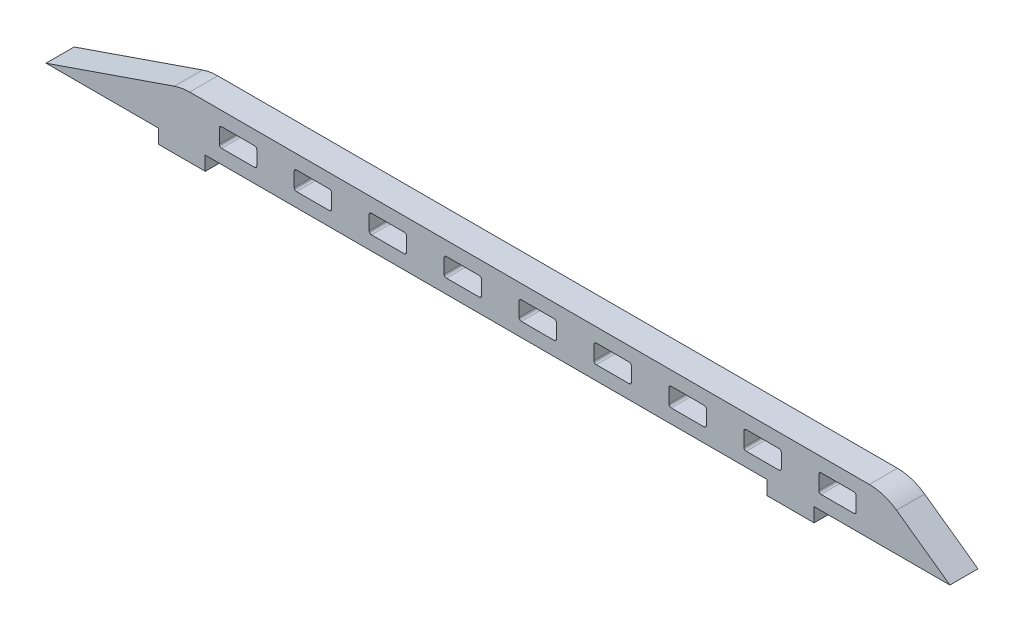
SolidWorks part; units mm, degrees
ref_plane "Front Plane" through (0, 0, 0) normal (0, 0, 1) x (1, 0, 0)
ref_plane "Top Plane" through (0, 0, 0) normal (0, 1, 0) x (1, 0, 0)
ref_plane "Right Plane" through (0, 0, 0) normal (1, 0, 0) x (0, 0, -1)
sketch "Sketch1" plane through (0, 0, 0) normal (0, 0, 1) x (1, 0, 0)
  line L0 (0, 0) -> (24, 0)
  line L1 (24, 0) -> (24, -3)
  line L2 (24, -3) -> (34, -3)
  line L3 (34, -3) -> (34, 0)
  line L4 (34, 0) -> (154, 0)
  line L5 (154, 0) -> (154, -3)
  line L6 (154, -3) -> (164, -3)
  line L7 (164, -3) -> (164, 0)
  line L8 (164, 0) -> (193, 0)
  line L9 (0, 0) -> (29, 10)
  line L10 (29, 10) -> (179, 10)
  line L11 (179, 10) -> (193, 0)
  line L12 (53.5, 7) -> (60.5, 7)
  line L13 (37.5, 7) -> (44.5, 7)
  line L14 (37, 6.5) -> (37, 3.5)
  line L15 (37.5, 3) -> (44.5, 3)
  line L16 (45, 6.5) -> (45, 3.5)
  line L17 (53, 6.5) -> (53, 3.5)
  line L18 (53.5, 3) -> (60.5, 3)
  line L19 (61, 6.5) -> (61, 3.5)
  line L20 (69.5, 7) -> (76.5, 7)
  line L21 (69, 6.5) -> (69, 3.5)
  line L22 (69.5, 3) -> (76.5, 3)
  line L23 (77, 6.5) -> (77, 3.5)
  line L24 (85.5, 7) -> (92.5, 7)
  line L25 (85, 6.5) -> (85, 3.5)
  line L26 (85.5, 3) -> (92.5, 3)
  line L27 (93, 6.5) -> (93, 3.5)
  line L28 (101.5, 7) -> (108.5, 7)
  line L29 (101, 6.5) -> (101, 3.5)
  line L30 (101.5, 3) -> (108.5, 3)
  line L31 (109, 6.5) -> (109, 3.5)
  line L32 (117.5, 7) -> (124.5, 7)
  line L33 (117, 6.5) -> (117, 3.5)
  line L34 (117.5, 3) -> (124.5, 3)
  line L35 (125, 6.5) -> (125, 3.5)
  line L36 (133.5, 7) -> (140.5, 7)
  line L37 (133, 6.5) -> (133, 3.5)
  line L38 (133.5, 3) -> (140.5, 3)
  line L39 (141, 6.5) -> (141, 3.5)
  line L40 (149.5, 7) -> (156.5, 7)
  line L41 (149, 6.5) -> (149, 3.5)
  line L42 (149.5, 3) -> (156.5, 3)
  line L43 (157, 6.5) -> (157, 3.5)
  line L44 (165.5, 7) -> (172.5, 7)
  line L45 (165, 6.5) -> (165, 3.5)
  line L46 (165.5, 3) -> (172.5, 3)
  line L47 (173, 6.5) -> (173, 3.5)
  arc A0 (44.5, 7) -> (45, 6.5) centre (44.5, 6.5) cw
  arc A1 (44.5, 3) -> (45, 3.5) centre (44.5, 3.5) ccw
  arc A2 (37, 3.5) -> (37.5, 3) centre (37.5, 3.5) ccw
  arc A3 (37.5, 7) -> (37, 6.5) centre (37.5, 6.5) ccw
  arc A4 (53.5, 7) -> (53, 6.5) centre (53.5, 6.5) ccw
  arc A5 (53, 3.5) -> (53.5, 3) centre (53.5, 3.5) ccw
  arc A6 (60.5, 3) -> (61, 3.5) centre (60.5, 3.5) ccw
  arc A7 (60.5, 7) -> (61, 6.5) centre (60.5, 6.5) cw
  arc A8 (69.5, 7) -> (69, 6.5) centre (69.5, 6.5) ccw
  arc A9 (69, 3.5) -> (69.5, 3) centre (69.5, 3.5) ccw
  arc A10 (76.5, 3) -> (77, 3.5) centre (76.5, 3.5) ccw
  arc A11 (76.5, 7) -> (77, 6.5) centre (76.5, 6.5) cw
  arc A12 (85.5, 7) -> (85, 6.5) centre (85.5, 6.5) ccw
  arc A13 (85, 3.5) -> (85.5, 3) centre (85.5, 3.5) ccw
  arc A14 (92.5, 3) -> (93, 3.5) centre (92.5, 3.5) ccw
  arc A15 (92.5, 7) -> (93, 6.5) centre (92.5, 6.5) cw
  arc A16 (101.5, 7) -> (101, 6.5) centre (101.5, 6.5) ccw
  arc A17 (101, 3.5) -> (101.5, 3) centre (101.5, 3.5) ccw
  arc A18 (108.5, 3) -> (109, 3.5) centre (108.5, 3.5) ccw
  arc A19 (108.5, 7) -> (109, 6.5) centre (108.5, 6.5) cw
  arc A20 (117.5, 7) -> (117, 6.5) centre (117.5, 6.5) ccw
  arc A21 (117, 3.5) -> (117.5, 3) centre (117.5, 3.5) ccw
  arc A22 (124.5, 3) -> (125, 3.5) centre (124.5, 3.5) ccw
  arc A23 (124.5, 7) -> (125, 6.5) centre (124.5, 6.5) cw
  arc A24 (133.5, 7) -> (133, 6.5) centre (133.5, 6.5) ccw
  arc A25 (133, 3.5) -> (133.5, 3) centre (133.5, 3.5) ccw
  arc A26 (140.5, 3) -> (141, 3.5) centre (140.5, 3.5) ccw
  arc A27 (140.5, 7) -> (141, 6.5) centre (140.5, 6.5) cw
  arc A28 (149.5, 7) -> (149, 6.5) centre (149.5, 6.5) ccw
  arc A29 (149, 3.5) -> (149.5, 3) centre (149.5, 3.5) ccw
  arc A30 (156.5, 3) -> (157, 3.5) centre (156.5, 3.5) ccw
  arc A31 (156.5, 7) -> (157, 6.5) centre (156.5, 6.5) cw
  arc A32 (165.5, 7) -> (165, 6.5) centre (165.5, 6.5) ccw
  arc A33 (165, 3.5) -> (165.5, 3) centre (165.5, 3.5) ccw
  arc A34 (172.5, 3) -> (173, 3.5) centre (172.5, 3.5) ccw
  arc A35 (172.5, 7) -> (173, 6.5) centre (172.5, 6.5) cw
  point P19 (45, 7)
  point P22 (45, 3)
  point P27 (37, 7)
  dimension "D13" = 0.5
  dimension "D1" = 10
  dimension "D2" = 3
  dimension "D3" = 120
  dimension "D4" = 10
  dimension "D5" = 193
  dimension "D6" = 24
  dimension "D7" = 150
  dimension "D8" = 14
  dimension "D9" = 4
  dimension "D10" = 8
  dimension "D11" = 3
  dimension "D12" = 3
  dimension "D15" = 8
  dimension "D14" = 9
extrude "Boss-Extrude1" add sketch "Sketch1" along normal blind 6
fillet "Fillet1" radius 10 2 edges at (179, 10, 3) (29, 10, 3)
